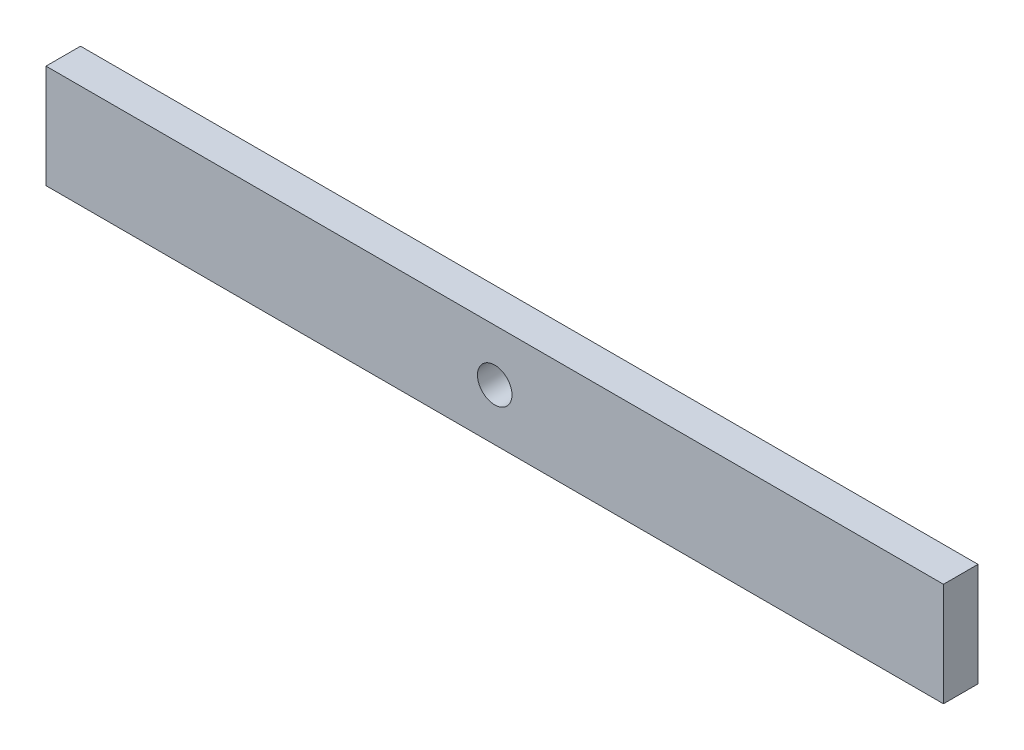
SolidWorks part; units mm, degrees
ref_plane "Plan de face" through (0, 0, 0) normal (0, 0, 1) x (1, 0, 0)
ref_plane "Plan de dessus" through (0, 0, 0) normal (0, 1, 0) x (1, 0, 0)
ref_plane "Plan de droite" through (0, 0, 0) normal (1, 0, 0) x (0, 0, -1)
sketch "Esquisse1" plane through (0, 0, 0) normal (0, 0, 1) x (1, 0, 0)
  line L1 (-130, -15) -> (130, -15)
  line L2 (-130, -15) -> (-130, 15)
  line L3 (-130, 15) -> (130, 15)
  line L4 (130, -15) -> (130, 15)
  line L5 (-130, -15) -> (130, 15) construction
  line L6 (-130, 15) -> (130, -15) construction
  point P0 (0, 0)
  dimension "D1" = 260
  dimension "D2" = 30
extrude "Boss.-Extru.1" add sketch "Esquisse1" along normal blind 10
sketch "Esquisse2" plane through (0, 0, 10) normal (0, 0, 1) x (1, 0, 0)
  circle A0 centre (0, 0) radius 5
extrude "Enlèv. mat.-Extru.1" cut sketch "Esquisse2" against normal blind 10
